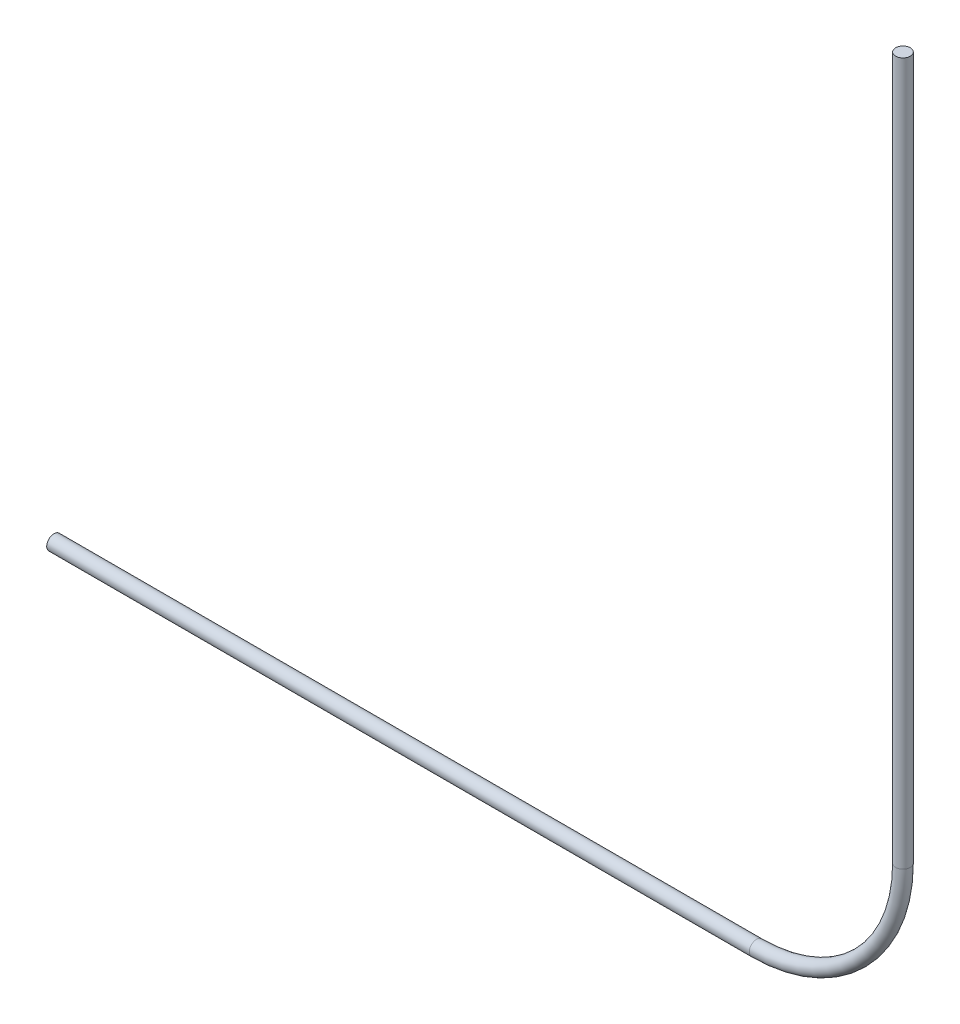
SolidWorks part; units mm, degrees
ref_plane "Front Plane" through (0, 0, 0) normal (0, 0, 1) x (1, 0, 0)
ref_plane "Top Plane" through (0, 0, 0) normal (0, 1, 0) x (1, 0, 0)
ref_plane "Right Plane" through (0, 0, 0) normal (1, 0, 0) x (0, 0, -1)
sketch "Sketch1" plane through (0, 0, 0) normal (0, 0, 1) x (1, 0, 0)
  line L0 (0, 127) -> (0, 736.6)
  line L1 (-127, 0) -> (-736.6, 0)
  arc A0 (0, 127) -> (-127, 0) centre (-127, 127) cw
  point P6 (0, 0)
  dimension "D1" = 127
  dimension "D2" = 609.6
  dimension "D3" = 609.6
sweep "Sweep1" add path "Sketch1" circular profile diameter 12.7 parameters "D3"=12.7
equation "\"Bend Radius\"= 5"
equation "\"Contact Length\"= 24"
equation "\"D1@Sketch1\"=\"Bend Radius\""
equation "\"Rebar Diameter\"= .5"
equation "\"D3@Sweep1\"=\"Rebar Diameter\""
